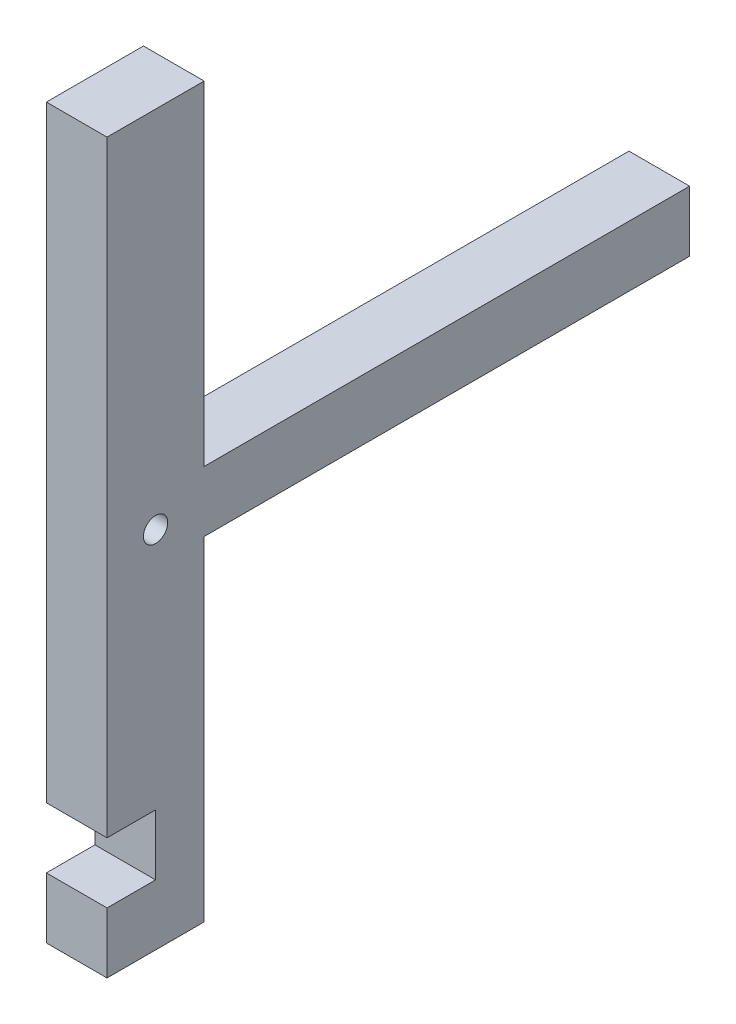
SolidWorks part; units mm, degrees
ref_plane "Front Plane" through (0, 0, 0) normal (0, 0, 1) x (1, 0, 0)
ref_plane "Top Plane" through (0, 0, 0) normal (0, 1, 0) x (1, 0, 0)
ref_plane "Right Plane" through (0, 0, 0) normal (1, 0, 0) x (0, 0, -1)
sketch "Elevator Paddle" plane through (0, 0, 0) normal (1, 0, 0) x (0, 0, -1)
  line L0 (-5.08, 0) -> (55.4696, 0) construction
  line L1 (-5.08, -38.1) -> (5.08, -38.1)
  line L2 (-5.08, -38.1) -> (-5.08, -31.75)
  line L3 (-5.08, 38.1) -> (5.08, 38.1)
  line L4 (5.08, -38.1) -> (5.08, -3.175)
  line L5 (-5.08, -38.1) -> (5.08, 38.1) construction
  line L6 (-5.08, 38.1) -> (5.08, -38.1) construction
  line L7 (5.08, -3.175) -> (55.88, -3.175)
  line L9 (5.08, 3.175) -> (55.88, 3.175)
  line L10 (55.88, -3.175) -> (55.88, 3.175)
  line L11 (0, 38.1) -> (0, -38.1) construction
  line L12 (-5.08, -31.75) -> (0, -31.75)
  line L13 (5.08, 3.175) -> (5.08, 38.1)
  line L14 (-5.08, -25.4) -> (0, -25.4)
  line L15 (0, -31.75) -> (0, -25.4)
  line L16 (-5.08, -25.4) -> (-5.08, 38.1)
  circle A0 centre (0, 0) radius 1.27
  point P0 (0, 0)
  point P14 (55.88, 0)
  dimension "D3" = 2.54
  dimension "D1" = 76.2
  dimension "D2" = 10.16
  dimension "D4" = 6.35
  dimension "D5" = 50.8
  dimension "D6" = 6.35
  dimension "D7" = 6.35
extrude "Boss-Extrude1" add sketch "Elevator Paddle" along normal blind 6.35 contours L16 L14 L15 L12 L2 L1 L4 L7 L10 L9 L13 L3 A0
equation "\"Ball Diameter\"= 1.75in"
equation "\"Sheet Thickness\"= 0.25in"
equation "\"Screw Diameter\"= .17in"
equation "\"Robot Diameter\"= 16in"
equation "\"Castor Screw Diameter\"= 0.22in"
equation "\"Wheel Diameter\" = 4in"
equation "\"Nut Diameter\" = 8.4mm"
equation "\"Nut Height\" = 2.9mm"
equation "\"Screw Height\" = 0.55in"
equation "\"D4@Elevator Paddle\"=\"Sheet Thickness\""
equation "\"D5@Elevator Paddle\"=\"Ball Diameter\"+0.25in"
equation "\"D6@Elevator Paddle\"=\"Sheet Thickness\""
equation "\"D7@Elevator Paddle\"=\"Sheet Thickness\""
equation "\"D1@Boss-Extrude1\"=\"Sheet Thickness\""
